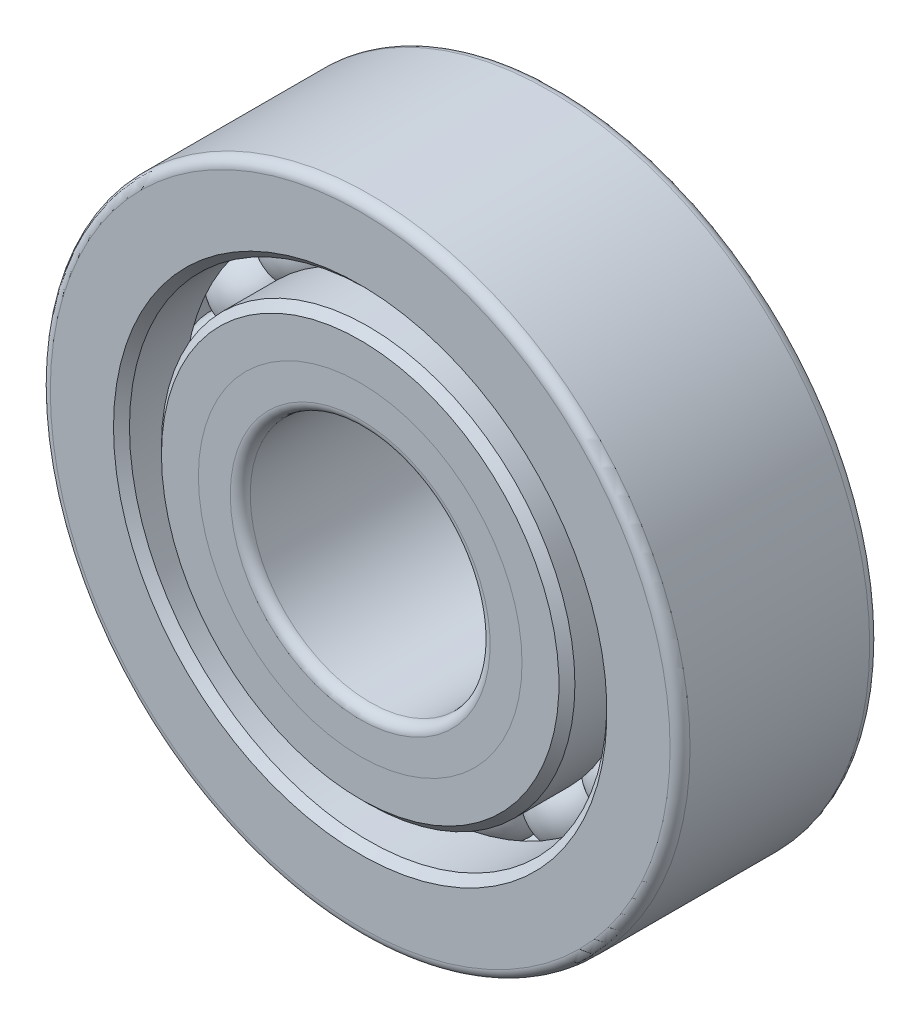
SolidWorks part; units mm, degrees
ref_plane "Front Plane" through (0, 0, 0) normal (0, 0, 1) x (1, 0, 0)
ref_plane "Top Plane" through (0, 0, 0) normal (0, 1, 0) x (1, 0, 0)
ref_plane "Right Plane" through (0, 0, 0) normal (1, 0, 0) x (0, 0, -1)
sketch "Sketch1" plane through (0, 0, 0) normal (1, 0, 0) x (0, 0, -1)
  line L0 (-3.9624, 0) -> (3.9624, 0) construction
  line L9 (0, 12.7) -> (0, 0) construction
  line L10 (-3.9624, 4.7625) -> (3.9624, 4.7625)
  line L11 (3.9624, 4.7625) -> (3.9624, 8.208)
  line L12 (3.9624, 8.208) -> (-3.9624, 8.208)
  line L13 (-3.9624, 8.208) -> (-3.9624, 4.7625)
  line L14 (-3.9624, 9.478) -> (3.9624, 9.478)
  line L15 (3.9624, 9.478) -> (3.9624, 12.7)
  line L16 (3.9624, 12.7) -> (-3.9624, 12.7)
  line L17 (-3.9624, 12.7) -> (-3.9624, 9.478)
  line L18 (-1.5875, 8.843) -> (1.5875, 8.843) construction
  line L20 (3.9624, 6.4245) -> (-3.9624, 6.4245) construction
  line L21 (0, 7.2555) -> (0, 6.4245)
  line L22 (0, 6.4245) -> (0, 5.5935)
  line L23 (0, 5.5935) -> (0, 4.7625)
  circle A0 centre (0, 8.843) radius 1.5875
  point P17 (0, 10.4305)
  dimension "ID" = 9.525
  dimension "OD" = 25.4
  dimension "Ball Diameter" = 3.175
  dimension "Ball Pattern Diameter" = 17.686
  dimension "D6" = 1.27
  dimension "Width" = 7.9248
sketch "Sketch2" plane through (0, 0, 0) normal (0, 0, 1) x (1, 0, 0)
  circle A0 centre (0, 0) radius 8.843 construction
  circle A1 centre (0, 8.843) radius 1.5875
  circle A2 centre (3.1945, 8.2459) radius 1.5875
  circle A3 centre (5.9575, 6.5351) radius 1.5875
  circle A4 centre (7.9159, 3.9417) radius 1.5875
  circle A5 centre (8.8053, 0.8159) radius 1.5875
  circle A6 centre (8.5054, -2.42) radius 1.5875
  circle A7 centre (7.0569, -5.3291) radius 1.5875
  circle A8 centre (4.6552, -7.5185) radius 1.5875
  circle A9 centre (1.6249, -8.6924) radius 1.5875
  circle A10 centre (-1.6249, -8.6924) radius 1.5875
  circle A11 centre (-4.6552, -7.5185) radius 1.5875
  circle A12 centre (-7.0569, -5.3291) radius 1.5875
  circle A13 centre (-8.5054, -2.42) radius 1.5875
  circle A15 centre (0, 0) radius 4.7625 construction
  circle A16 centre (0, 0) radius 12.7 construction
  circle A17 centre (-8.8053, 0.8159) radius 1.5875
  circle A18 centre (-7.9159, 3.9417) radius 1.5875
  circle A19 centre (-5.9575, 6.5351) radius 1.5875
  circle A20 centre (-3.1945, 8.2459) radius 1.5875
  point P36 (0, 0)
  dimension "ID" = 9.525
  dimension "OD" = 25.4
  dimension "No. of Balls" = 17
sketch "Sketch3" plane through (0, 0, 0) normal (1, 0, 0) x (0, 0, -1)
  line L1 (3.9624, 4.7625) -> (3.9624, 8.208) construction
  line L2 (-3.9624, 8.208) -> (-3.9624, 4.7625) construction
  line L3 (3.9624, 8.208) -> (-3.9624, 8.208) construction
  line L5 (3.9624, 4.7625) -> (3.9624, 8.208)
  line L6 (-3.9624, 8.208) -> (-3.9624, 4.7625)
  line L7 (3.9624, 8.208) -> (-3.9624, 8.208)
  line L8 (-3.9624, 12.7) -> (-3.9624, 9.478) construction
  line L9 (3.9624, 12.7) -> (-3.9624, 12.7) construction
  line L10 (3.9624, 9.478) -> (3.9624, 12.7) construction
  line L11 (-3.9624, 9.478) -> (3.9624, 9.478) construction
  line L12 (-3.9624, 12.7) -> (-3.9624, 9.478)
  line L13 (3.9624, 12.7) -> (-3.9624, 12.7)
  line L14 (3.9624, 9.478) -> (3.9624, 12.7)
  line L15 (-3.9624, 9.478) -> (3.9624, 9.478)
  line L16 (-3.9624, 4.7625) -> (3.9624, 4.7625) construction
  line L17 (-3.9624, 4.7625) -> (3.9624, 4.7625)
revolve "Revolve2" add sketch "Sketch3" angle 360 about L0
sketch "Sketch4" plane through (0, 0, 0) normal (1, 0, 0) x (0, 0, -1)
  circle A0 centre (0, 8.843) radius 1.5875 construction
  circle A1 centre (0, 8.843) radius 1.5875
revolve "Cut-Revolve1" cut sketch "Sketch4" angle 360 about L0
sketch "Sketch5" plane through (0, 0, 0) normal (1, 0, 0) x (0, 0, -1)
  line L0 (-1.5875, 8.843) -> (1.5875, 8.843) construction
  line L1 (-1.5875, 8.843) -> (1.5875, 8.843)
  circle A0 centre (0, 8.843) radius 1.5875 construction
  arc A1 (1.5875, 8.843) -> (-1.5875, 8.843) centre (0, 8.843) ccw
revolve "Revolve3" add sketch "Sketch5" angle 360 about L18
pattern_circular "CirPattern1" count 17 over 360 about axis through (0, 0, 0) along (0, 0, 1) of bodies 109
fillet "Fillet1" radius 0.3962 2 edges at (12.7, 0, 3.9624) (12.7, 0, -3.9624)
fillet "Fillet2" radius 0.3962 2 edges at (4.7625, 0, -3.9624) (4.7625, 0, 3.9624)
chamfer "Chamfer1" distance 0.317 angle 45 2 edges at (9.478, 0, -3.9624) (9.478, 0, 3.9624)
chamfer "Chamfer2" distance 0.317 angle 45 2 edges at (8.208, 0, 3.9624) (8.208, 0, -3.9624)
sketch "Split Line" plane through (0, 0, 0) normal (0, 0, 1) x (1, 0, 0)
  circle A0 centre (0, 0) radius 6.4245
split "Split1" trim tools "Split Line" bodies to split 108 resulting bodies 128 129
equation "\"D1@CirPattern1\"=\"No. of Balls@Sketch2\""
equation "\"D6@Sketch1\"=\"Ball Diameter@Sketch1\"*0.4"
equation "\"D1@Fillet1\"=\"Width@Sketch1\"/20"
equation "\"D1@Fillet2\"=\"Width@Sketch1\"/20"
equation "\"D1@Chamfer1\"=\"Width@Sketch1\"/25"
equation "\"D1@Chamfer2\"=\"Width@Sketch1\"/25"
equation "\"ID@Sketch2\"=\"ID@Sketch1\""
equation "\"OD@Sketch2\" = \"OD@Sketch1\""
